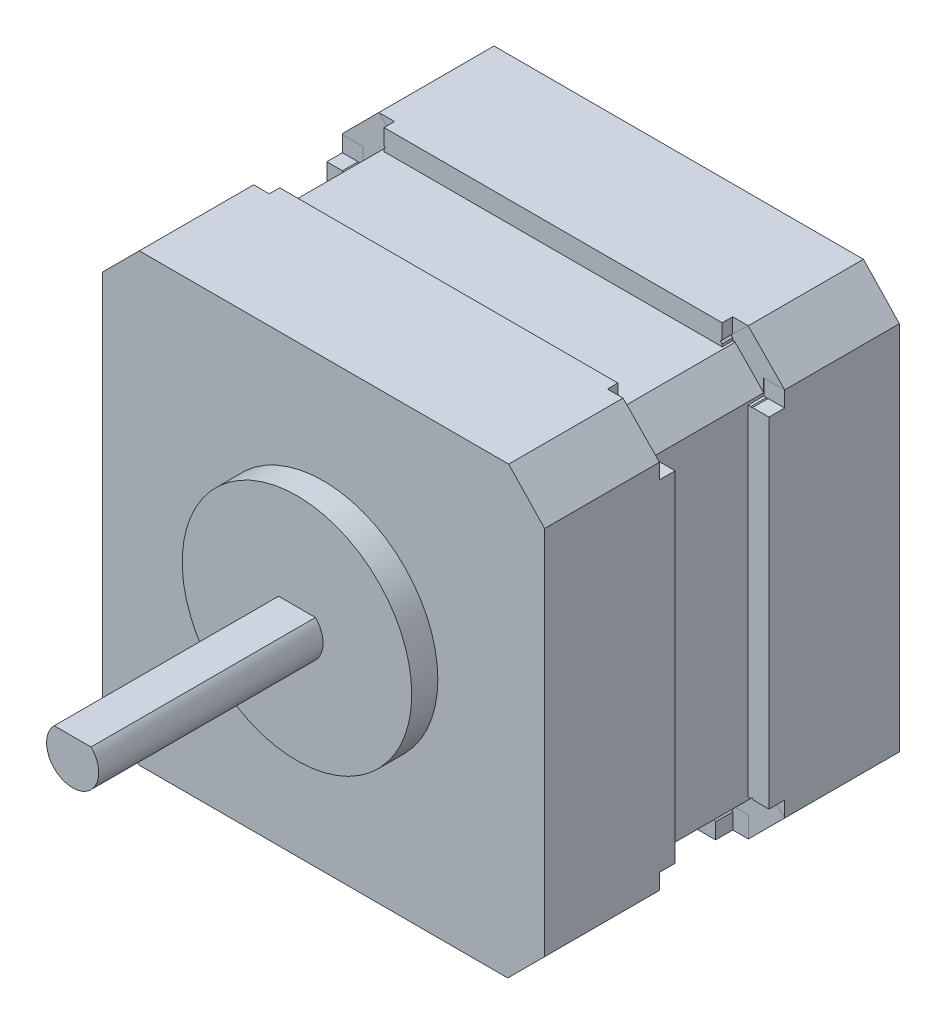
SolidWorks part; units mm, degrees
ref_plane "Front Plane" through (0, 0, 0) normal (0, 0, 1) x (1, 0, 0)
ref_plane "Top Plane" through (0, 0, 0) normal (0, 1, 0) x (1, 0, 0)
ref_plane "Right Plane" through (0, 0, 0) normal (1, 0, 0) x (0, 0, -1)
sketch "Sketch1" plane through (0, 0, 0) normal (0, 0, 1) x (1, 0, 0)
  line L0 (-17.6145, 21.2641) -> (-21.15, 17.7286)
  line L1 (-17.6145, 21.2641) -> (17.7906, 21.2641)
  line L2 (-21.15, 17.7286) -> (-21.15, -17.899)
  line L3 (-17.6145, -21.4346) -> (17.6992, -21.4346)
  line L4 (21.2347, 17.6394) -> (21.2347, -17.899)
  line L5 (-19.4393, 19.4393) -> (19.5669, -19.5669) construction
  line L6 (-19.5245, -19.5245) -> (19.483, 19.483) construction
  line L7 (-21.15, -17.899) -> (-17.6145, -21.4346)
  line L8 (21.2347, -17.899) -> (17.6992, -21.4346)
  line L9 (21.2347, 17.6394) -> (17.7906, 21.2641)
  point P0 (0, 0)
  dimension "D1" = 133.537
  dimension "D2" = 135
  dimension "D3" = 135
  dimension "D4" = 135
  dimension "D5" = 5
  dimension "D6" = 5
  dimension "D7" = 5
  dimension "D8" = 5
extrude "Boss-Extrude1" add sketch "Sketch1" along normal blind 34
sketch "Sketch2" plane through (0, 0, 34) normal (0, 0, 1) x (1, 0, 0)
  circle A0 centre (0, 0) radius 11
extrude "Boss-Extrude2" add sketch "Sketch2" along normal blind 2.5 contours A0
sketch "Sketch3" plane through (0, 0, 36.5) normal (0, 0, 1) x (1, 0, 0)
  circle A0 centre (0, 0) radius 2.5
extrude "Boss-Extrude3" add sketch "Sketch3" along normal blind 21.5
sketch "Sketch6" plane through (0, 21.2641, 0) normal (0, 1, 0) x (1, 0, 0)
  line L0 (-17.6145, -11.0395) -> (-17.6145, -23.0395)
  line L1 (-17.6145, -34) -> (-17.6145, 0) construction
  line L2 (-17.6145, -11.0395) -> (-16.1145, -11.0395)
  line L3 (-16.1145, -11.0395) -> (-16.1145, -12.0395)
  line L4 (-16.1145, -12.0395) -> (16.2906, -12.0395)
  line L5 (16.2906, -12.0395) -> (16.2906, -11.0395)
  line L6 (16.2906, -11.0395) -> (17.7906, -11.0395)
  line L7 (17.7906, -34) -> (17.7906, 0) construction
  line L8 (17.7906, -11.0395) -> (17.7906, -23.0395)
  line L9 (17.7906, -23.0395) -> (16.2906, -23.0395)
  line L10 (16.2906, -23.0395) -> (16.2906, -22.0395)
  line L11 (16.2906, -22.0395) -> (-16.1145, -22.0395)
  line L12 (-16.1145, -22.0395) -> (-16.1145, -23.0395)
  line L13 (-16.1145, -23.0395) -> (-17.6145, -23.0395)
  point P5 (-17.6145, -17.0395)
  dimension "D1" = 12
  dimension "D2" = 1.5
  dimension "D3" = 1.5
  dimension "D4" = 1
  dimension "D5" = 1
  dimension "D6" = 1
  dimension "D7" = 1
sketch "Sketch7" plane through (21.2347, 0, 0) normal (1, 0, 0) x (0, 0, -1)
  line L0 (-22.9974, 17.6818) -> (-10.9974, 17.6394)
  line L1 (-34, 17.6394) -> (0, 17.6394) construction
  line L2 (-10.9974, 17.6394) -> (-10.9974, 16.1394)
  line L3 (-10.9974, 16.1394) -> (-12.4974, 16.1394)
  line L4 (-12.4974, 16.1394) -> (-12.4974, -16.399)
  line L5 (-12.4974, -16.399) -> (-10.9974, -16.399)
  line L6 (-10.9974, -16.399) -> (-10.9974, -17.899)
  line L7 (-34, -17.899) -> (0, -17.899) construction
  line L8 (-10.9974, -17.899) -> (-22.9974, -17.899)
  line L9 (-22.9974, -17.899) -> (-22.9974, -16.399)
  line L10 (-22.9974, -16.399) -> (-21.4974, -16.399)
  line L11 (-21.4974, -16.399) -> (-21.4974, 16.1818)
  line L12 (-21.4974, 16.1818) -> (-22.9974, 16.1818)
  line L13 (-22.9974, 17.6818) -> (-22.9974, 16.1818)
  point P5 (-16.9974, 17.6606)
  dimension "D3" = 1.5
  dimension "D1" = 1.5
  dimension "D2" = 1.5
  dimension "D4" = 1.5
  dimension "D5" = 12
  dimension "D6" = 1.5
  dimension "1.5" = 1.5
  dimension "D7" = 1.5
  dimension "D8" = 1.5
extrude "Cut-Extrude3" cut sketch "Sketch7" against normal blind 2
extrude "Cut-Extrude4" cut sketch "Sketch6" against normal blind 2
sketch "Sketch8" plane through (19.9677, 18.9728, 0) normal (0.7249, 0.6888, 0) x (0, 0, -1)
  line L0 (-23.0395, 3.1606) -> (-22.9974, -1.781)
  line L1 (-22.9974, -1.781) -> (-10.9974, -1.8394)
  line L2 (-10.9974, -1.8394) -> (-11.0395, 3.1606)
  line L3 (-11.0395, 3.1606) -> (-23.0395, 3.1606)
extrude "Cut-Extrude5" cut sketch "Sketch8" against normal blind 2.3
sketch "Sketch9" plane through (0, -21.4346, 0) normal (0, -1, 0) x (1, 0, 0)
  line L0 (17.6992, 22.9327) -> (17.6992, 10.9327)
  line L1 (17.6992, 34) -> (17.6992, 0) construction
  line L2 (17.6992, 10.9327) -> (16.1992, 10.9327)
  line L3 (16.1992, 10.9327) -> (16.1992, 12.5808)
  line L4 (16.1992, 12.5808) -> (-16.1145, 12.5808)
  line L5 (-16.1145, 12.5808) -> (-16.1145, 10.9327)
  line L6 (-16.1145, 10.9327) -> (-17.6145, 10.9327)
  line L7 (-17.6145, 34) -> (-17.6145, 0) construction
  line L8 (-17.6145, 10.9327) -> (-17.6145, 22.9327)
  line L9 (-17.6145, 22.9327) -> (-16.1145, 22.9327)
  line L10 (-16.1145, 22.9327) -> (-16.1145, 20.6868)
  line L11 (-16.1145, 20.6868) -> (16.1992, 20.6868)
  line L12 (16.1992, 20.6868) -> (16.1992, 22.9327)
  line L13 (16.1992, 22.9327) -> (17.6992, 22.9327)
  point P5 (17.6992, 16.9327)
  dimension "D1" = 12
  dimension "D2" = 12
  dimension "D3" = 1.5
  dimension "1.5" = 1.5
  dimension "D4" = 1.5
  dimension "D5" = 1.5
sketch "Sketch10" plane through (19.5669, -19.5669, 0) normal (0.7071, -0.7071, 0) x (0, 0, -1)
  line L0 (-22.9974, 2.3587) -> (-22.9327, -2.6413)
  line L1 (-22.9327, -2.6413) -> (-10.9327, -2.6413)
  line L2 (-10.9327, -2.6413) -> (-10.9974, 2.3587)
  line L3 (-10.9974, 2.3587) -> (-22.9974, 2.3587)
extrude "Cut-Extrude6" cut sketch "Sketch10" against normal blind 2.3
extrude "Cut-Extrude7" cut sketch "Sketch9" against normal blind 2
sketch "Sketch13" plane through (-21.15, 0, 0) normal (-1, 0, 0) x (0, 0, 1)
  line L0 (22.9974, 17.6394) -> (10.9974, 17.6394)
  line L1 (10.9974, 17.6394) -> (10.9974, 16.1394)
  line L2 (10.9974, 16.1394) -> (12.4974, 16.1394)
  line L3 (12.4974, 16.1394) -> (12.4974, -16.399)
  line L4 (12.4974, -16.399) -> (10.9974, -16.399)
  line L5 (10.9974, -16.399) -> (10.9974, -17.899)
  line L6 (10.9974, -17.899) -> (22.9974, -17.899)
  line L7 (22.9974, -17.899) -> (22.9974, -16.399)
  line L8 (22.9974, -16.399) -> (21.4974, -16.399)
  line L9 (21.4974, -16.399) -> (21.4974, 16.1818)
  line L10 (21.4974, 16.1818) -> (22.9974, 16.1818)
  line L11 (22.9974, 16.1818) -> (22.9974, 17.6394)
extrude "Cut-Extrude9" cut sketch "Sketch13" against normal blind 2
sketch "Sketch14" plane through (-19.4393, 19.4393, 0) normal (-0.7071, 0.7071, 0) x (0, 0, 1)
  line L0 (11.0395, 2.5807) -> (10.9974, -2.4824)
  line L1 (10.9974, -2.4824) -> (22.9974, -2.4824)
  line L2 (22.9974, -2.4824) -> (23.0395, 2.5807)
  line L3 (23.0395, 2.5807) -> (11.0395, 2.5807)
extrude "Cut-Extrude10" cut sketch "Sketch14" against normal blind 2.3
sketch "Sketch15" plane through (-19.5245, -19.5245, 0) normal (-0.7071, -0.7071, 0) x (0, 0, 1)
  line L0 (10.9974, 2.2988) -> (10.9327, -2.7012)
  line L1 (10.9327, -2.7012) -> (22.9327, -2.7012)
  line L2 (22.9327, -2.7012) -> (22.9974, 2.2988)
  line L3 (22.9974, 2.2988) -> (10.9974, 2.2988)
extrude "Cut-Extrude11" cut sketch "Sketch15" against normal blind 2.3
sketch "Sketch16" plane through (0, 0, 58) normal (0, 0, 1) x (1, 0, 0)
  line L0 (-1.7647, 1.7709) -> (1.7647, 1.7709)
  circle A0 centre (0, 0) radius 2.5 construction
  arc A1 (-1.7647, 1.7709) -> (1.7647, 1.7709) centre (0, 0) cw
extrude "Cut-Extrude12" cut sketch "Sketch16" against normal blind 21.5
